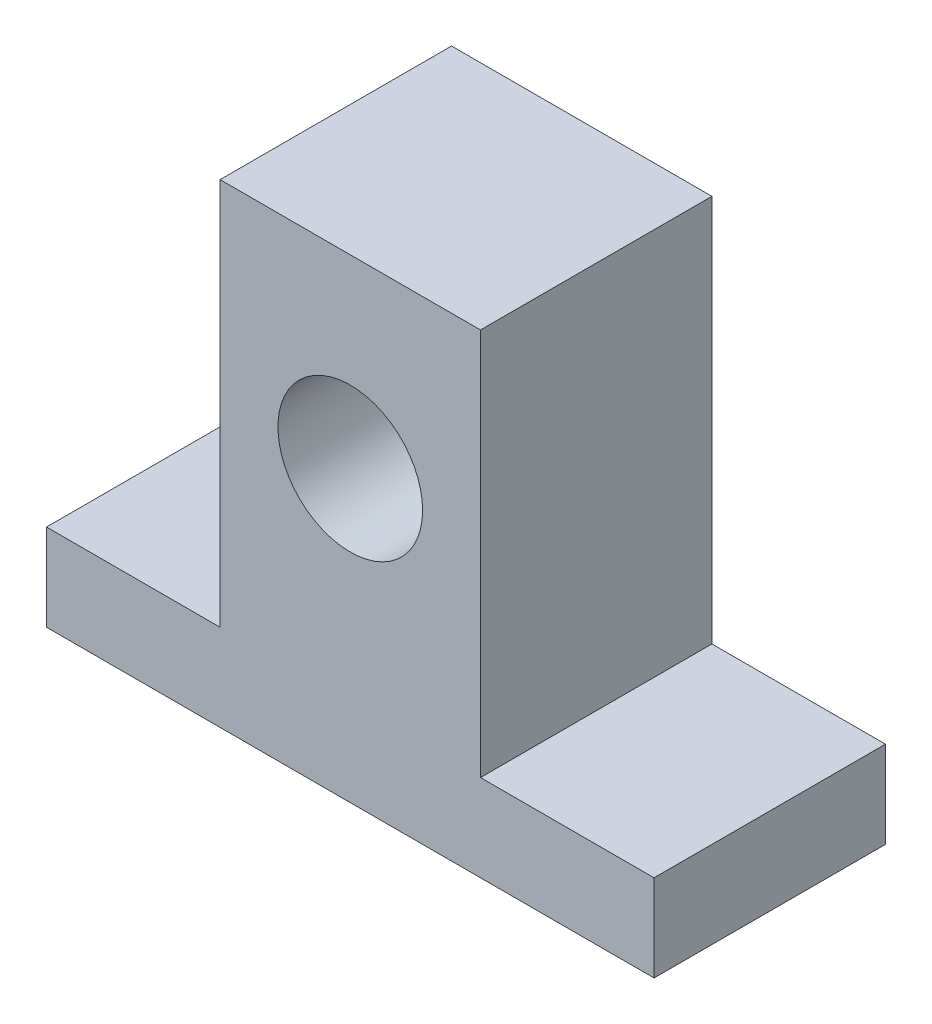
SolidWorks part; units mm, degrees
ref_plane "前基準面" through (0, 0, 0) normal (0, 0, 1) x (1, 0, 0)
ref_plane "上基準面" through (0, 0, 0) normal (0, 1, 0) x (1, 0, 0)
ref_plane "右基準面" through (0, 0, 0) normal (1, 0, 0) x (0, 0, -1)
sketch "草圖1" plane through (0, 0, 0) normal (0, 0, 1) x (1, 0, 0)
  line L0 (0, 0) -> (0, 32.8) construction
  line L1 (9, 32.8) -> (-9, 32.8)
  line L2 (-9, 32.8) -> (-9, 6)
  line L3 (-9, 6) -> (-21, 6)
  line L4 (-21, 6) -> (-21, 0)
  line L5 (-21, 0) -> (21, 0)
  line L6 (21, 6) -> (21, 0)
  line L7 (9, 6) -> (21, 6)
  line L8 (9, 32.8) -> (9, 6)
  circle A0 centre (0, 20) radius 5
  dimension "D6" = 10
  dimension "D1" = 32.8
  dimension "D2" = 21
  dimension "D3" = 6
  dimension "D4" = 12
  dimension "D5" = 26.8
  dimension "D7" = 20
extrude "填料-伸長1" add sketch "草圖1" along normal blind 16
sketch "草圖2" plane through (0, 0, 0) normal (0, -1, 0) x (1, 0, 0)
  line L0 (21, 8) -> (-21, 8) construction
  line L1 (21, 16) -> (21, 0) construction
  line L2 (-21, 16) -> (-21, 0) construction
